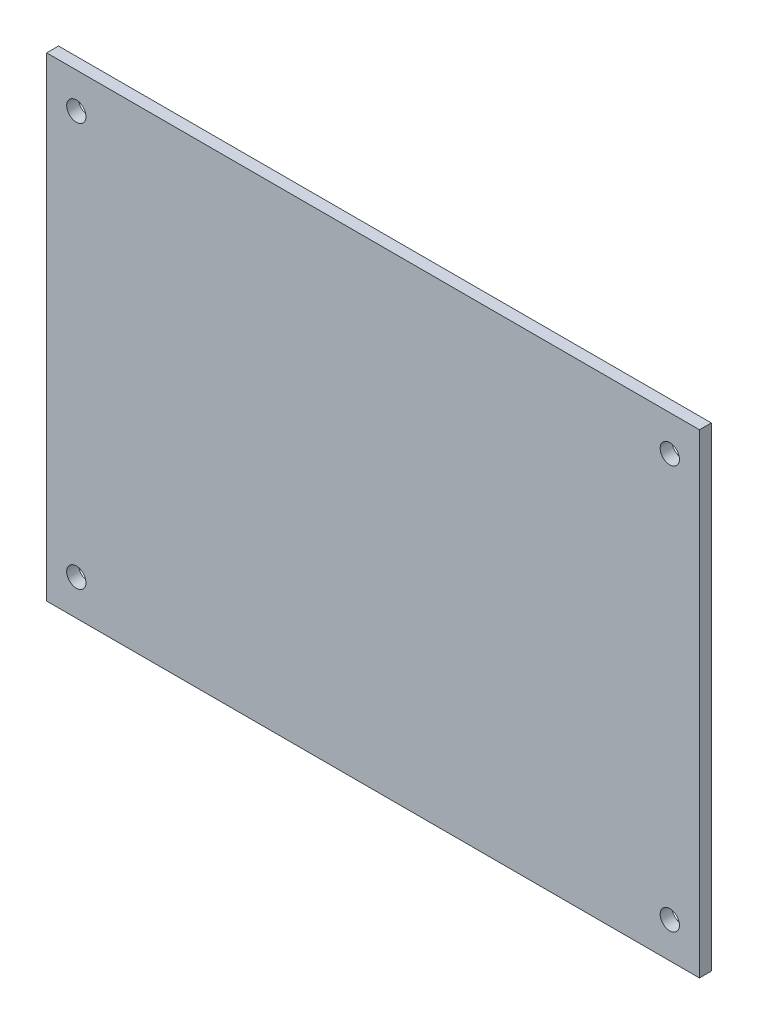
SolidWorks part; units mm, degrees
ref_plane "Front Plane" through (0, 0, 0) normal (0, 0, 1) x (1, 0, 0)
ref_plane "Top Plane" through (0, 0, 0) normal (0, 1, 0) x (1, 0, 0)
ref_plane "Right Plane" through (0, 0, 0) normal (1, 0, 0) x (0, 0, -1)
sketch "Sketch1" plane through (0, 0, 0) normal (0, 0, 1) x (1, 0, 0)
  line L1 (-55, 40) -> (55, 40)
  line L2 (-55, 40) -> (-55, -40)
  line L3 (-55, -40) -> (55, -40)
  line L4 (55, 40) -> (55, -40)
  line L5 (-55, 40) -> (55, -40) construction
  line L6 (-55, -40) -> (55, 40) construction
  point P0 (0, 0)
  dimension "D1" = 110
  dimension "D2" = 80
extrude "Boss-Extrude1" add sketch "Sketch1" against normal blind 2
sketch "Sketch2" plane through (0, 0, 0) normal (0, 0, 1) x (1, 0, 0)
  line L0 (0, 0) -> (50000, 0) construction
  line L1 (0, 0) -> (0, 50000) construction
  circle A0 centre (-50, 34) radius 1.6246
  circle A1 centre (50, 34) radius 1.6246
  circle A2 centre (50, -34) radius 1.6246
  circle A3 centre (-50, -34) radius 1.6246
  dimension "D1" = 50
  dimension "D2" = 34
extrude "Cut-Extrude1" cut sketch "Sketch2" against normal through all
